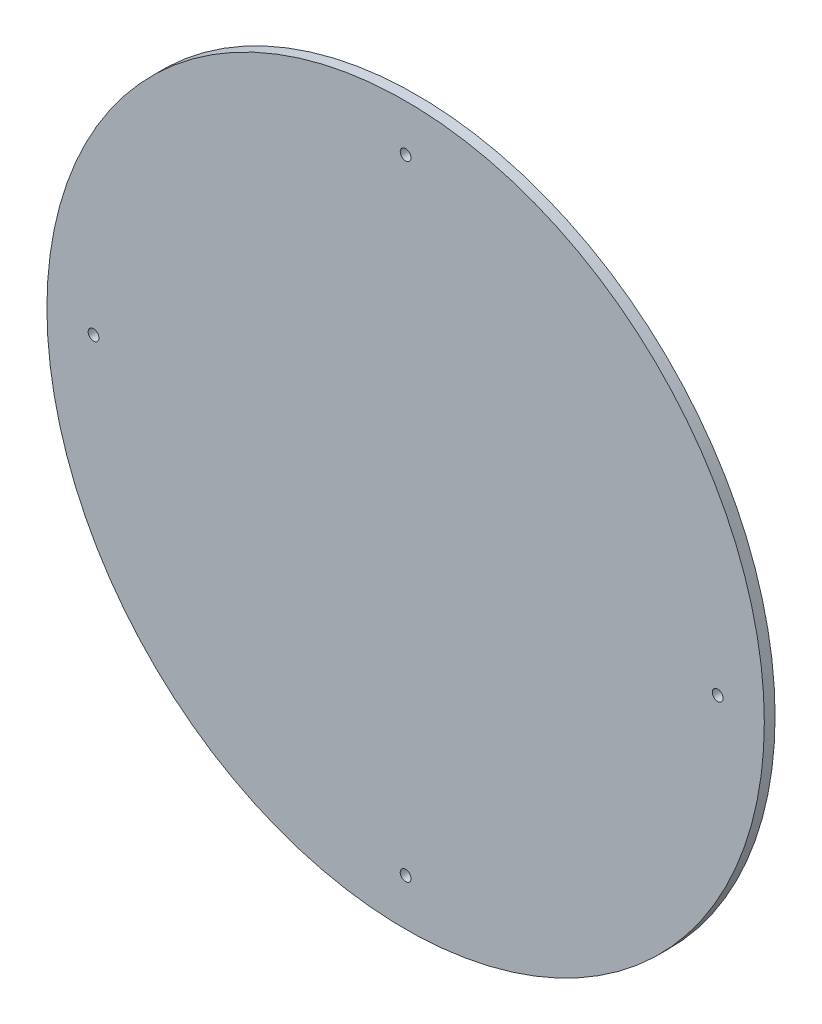
SolidWorks part; units mm, degrees
ref_plane "Alzado" through (0, 0, 0) normal (0, 0, 1) x (1, 0, 0)
ref_plane "Planta" through (0, 0, 0) normal (0, 1, 0) x (1, 0, 0)
ref_plane "Vista lateral" through (0, 0, 0) normal (1, 0, 0) x (0, 0, -1)
sketch "Croquis1" plane through (0, 0, 0) normal (0, 0, 1) x (1, 0, 0)
  line L0 (0, -100) -> (0, 100) construction
  line L1 (-100, 0) -> (100, 0) construction
  line L2 (-19, 80.6103) -> (19, 80.6103) construction
  line L3 (50.6103, 19) -> (80.6103, 19) construction
  line L4 (-23.5, 94.1103) -> (23.5, 94.1103) construction
  line L5 (-23.5, 94.1103) -> (-23.5, 37.1103) construction
  line L6 (-23.5, 37.1103) -> (23.5, 37.1103) construction
  line L7 (23.5, 94.1103) -> (23.5, 37.1103) construction
  circle A0 centre (0, 0) radius 100
  circle A1 centre (-19, 80.6103) radius 2
  circle A2 centre (19, 80.6103) radius 2
  circle A3 centre (-19, 50.6103) radius 2
  circle A4 centre (19, 50.6103) radius 2
  circle A5 centre (80.6103, 19) radius 2
  circle A6 centre (80.6103, -19) radius 2
  circle A7 centre (50.6103, 19) radius 2
  circle A8 centre (50.6103, -19) radius 2
  circle A9 centre (19, -80.6103) radius 2
  circle A10 centre (-19, -80.6103) radius 2
  circle A11 centre (19, -50.6103) radius 2
  circle A12 centre (-19, -50.6103) radius 2
  circle A13 centre (-80.6103, -19) radius 2
  circle A14 centre (-80.6103, 19) radius 2
  circle A15 centre (-50.6103, -19) radius 2
  circle A16 centre (-50.6103, 19) radius 2
  point P15 (0, 37.1103)
  point P20 (0, 80.6103)
  point P21 (0, 0)
  point P26 (0, 0)
  point P27 (0, 0)
  point P48 (0, 0)
  point P49 (0, 0)
  dimension "D1" = 200
  dimension "D2" = 4
  dimension "D3" = 34
  dimension "D4" = 26
  dimension "D6" = 3
  dimension "D5" = 11.5
  dimension "D7" = 57
  dimension "D8" = 47
  dimension "D10" = 19
  dimension "D11" = 50.6103
  dimension "D9" = 4
extrude "Saliente-Extruir1" add sketch "Croquis1" along normal blind 3 contours A0
sketch "Croquis5" plane through (0, 0, 3) normal (0, 0, 1) x (1, 0, 0)
  circle A0 centre (0, 87) radius 1.5
  circle A1 centre (87, 0) radius 1.5
  circle A2 centre (0, -87) radius 1.5
  circle A3 centre (0, 0) radius 100 construction
  circle A4 centre (-87, 0) radius 1.5
  point P4 (0, 0)
  point P6 (0, 0)
  point P7 (0, 0)
  point P14 (0, 0)
  dimension "D2" = 3
  dimension "D1" = 13
  dimension "D4" = 13
  dimension "D3" = 4
extrude "Cortar-Extruir4" cut sketch "Croquis5" against normal up to surface (3 mm away) up to face at (100, 0, 0)
